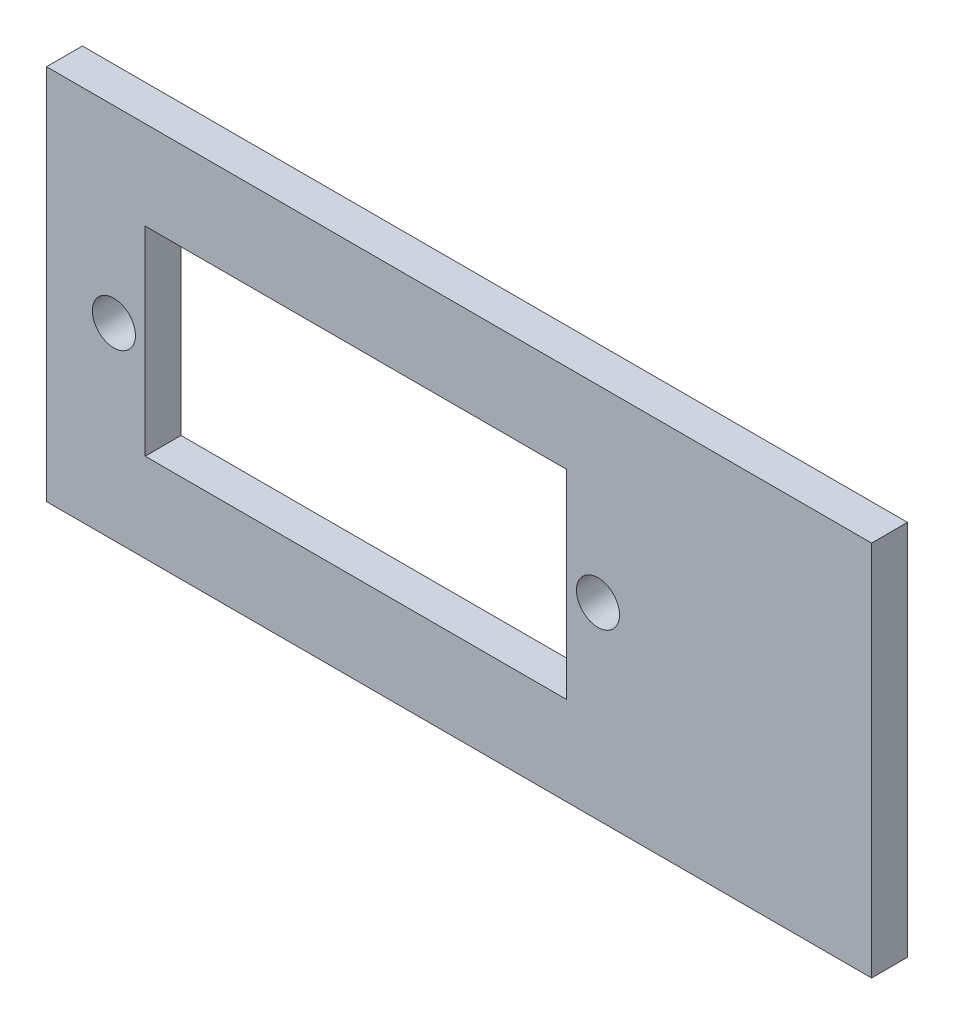
SolidWorks part; units mm, degrees
material "Plain Carbon Steel"
ref_plane "Front Plane" through (0, 0, 0) normal (0, 0, 1) x (1, 0, 0)
ref_plane "Top Plane" through (0, 0, 0) normal (0, 1, 0) x (1, 0, 0)
ref_plane "Right Plane" through (0, 0, 0) normal (1, 0, 0) x (0, 0, -1)
sketch "Sketch1" plane through (0, 0, 0) normal (0, 0, 1) x (1, 0, 0)
  line L1 (115, 52.5) -> (-115, 52.5)
  line L2 (115, 52.5) -> (115, -52.5)
  line L3 (115, -52.5) -> (-115, -52.5)
  line L4 (-115, 52.5) -> (-115, -52.5)
  line L5 (115, 52.5) -> (-115, -52.5) construction
  line L6 (115, -52.5) -> (-115, 52.5) construction
  point P0 (0, 0)
  dimension "D1" = 105
  dimension "D2" = 230
extrude "Boss-Extrude1" add sketch "Sketch1" along normal blind 10
sketch "Sketch2" plane through (0, 0, 10) normal (0, 0, 1) x (1, 0, 0)
  line L0 (-171.9481, 0) -> (164.4558, 0) construction
  line L1 (0, 89.3456) -> (0, -95.714) construction
  line L4 (-87.5, 27.775) -> (30, 27.775)
  line L5 (-87.5, 27.775) -> (-87.5, -27.775)
  line L6 (-87.5, -27.775) -> (30, -27.775)
  line L7 (30, 27.775) -> (30, -27.775)
  line L8 (-87.5, 27.775) -> (30, -27.775) construction
  line L9 (-87.5, -27.775) -> (30, 27.775) construction
  line L10 (-115, 52.5) -> (-115, -52.5) construction
  line L11 (-28.75, 27.775) -> (-28.75, -27.775) construction
  circle A0 centre (38.725, 0) radius 6
  circle A1 centre (-96.225, 0) radius 6
  point P5 (-28.75, 0)
  dimension "D4" = 12
  dimension "D5" = 12
  dimension "D1" = 117.5
  dimension "D2" = 55.55
  dimension "D3" = 27.5
  dimension "D6" = 134.95
extrude "Cut-Extrude3" cut sketch "Sketch2" against normal blind 10
